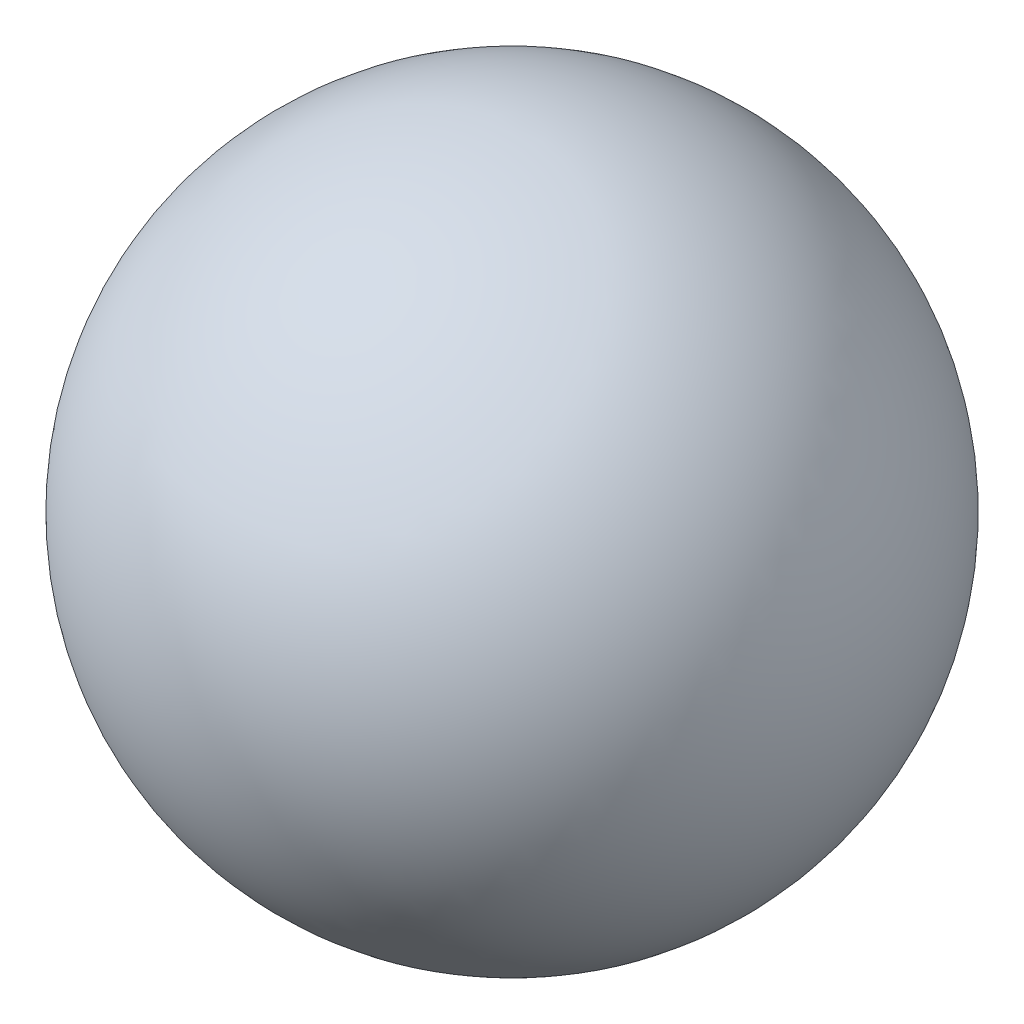
SolidWorks part; units mm, degrees
ref_plane "Plan de face" through (0, 0, 0) normal (0, 0, 1) x (1, 0, 0)
ref_plane "Plan de dessus" through (0, 0, 0) normal (0, 1, 0) x (1, 0, 0)
ref_plane "Plan de droite" through (0, 0, 0) normal (1, 0, 0) x (0, 0, -1)
sketch "Esquisse1" plane through (0, 0, 0) normal (0, 0, 1) x (1, 0, 0)
  line L0 (0, 30) -> (0, -30) construction
  line L1 (0, 30) -> (0, -30)
  arc A0 (0, 30) -> (0, -30) centre (0, 0) cw
  dimension "D1" = 30
revolve "Révolution1" add sketch "Esquisse1" angle 360 about L0
